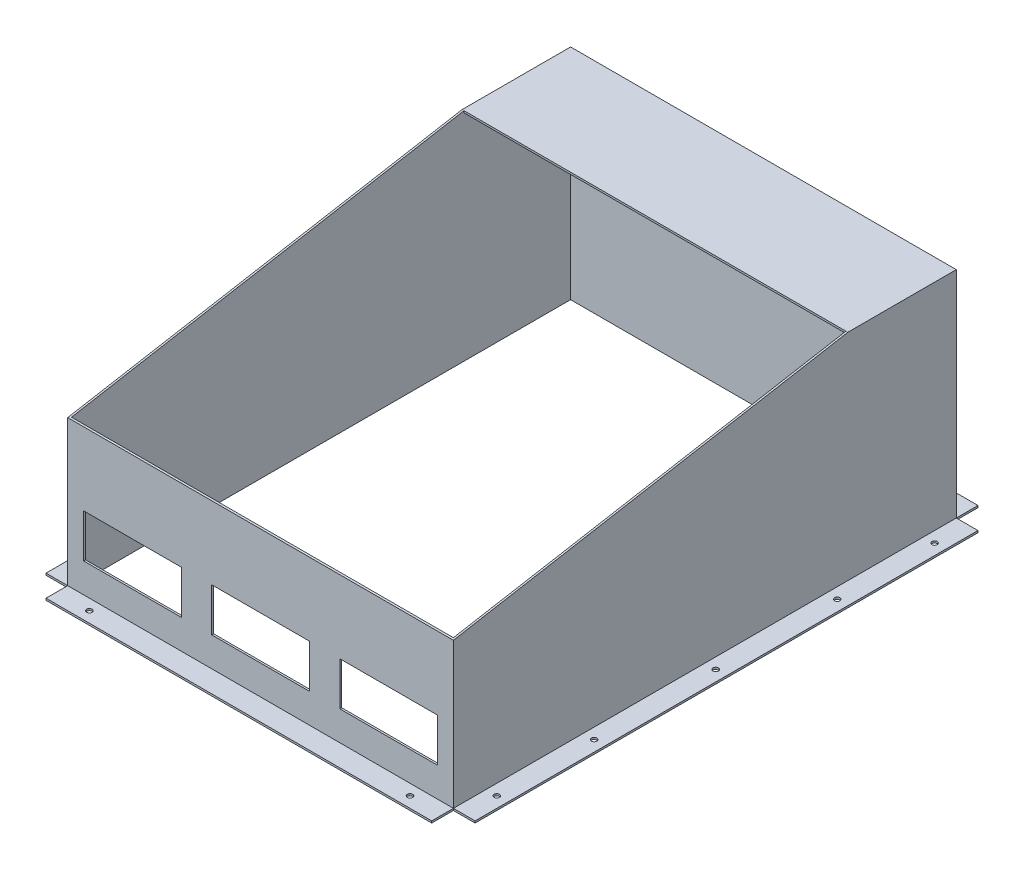
SolidWorks part; units mm, degrees
ref_plane "Alzado" through (0, 0, 0) normal (0, 0, 1) x (1, 0, 0)
ref_plane "Planta" through (0, 0, 0) normal (0, 1, 0) x (1, 0, 0)
ref_plane "Vista lateral" through (0, 0, 0) normal (1, 0, 0) x (0, 0, -1)
sketch "Croquis1" plane through (0, 0, 0) normal (0, 1, 0) x (1, 0, 0)
  line L1 (-177.75, 231.75) -> (177.75, 231.75)
  line L2 (-177.75, 231.75) -> (-177.75, -231.75)
  line L3 (-177.75, -231.75) -> (177.75, -231.75)
  line L4 (177.75, 231.75) -> (177.75, -231.75)
  line L5 (-177.75, 231.75) -> (177.75, -231.75) construction
  line L6 (-177.75, -231.75) -> (177.75, 231.75) construction
  point P0 (0, 0)
  dimension "D1" = 355.5
  dimension "D2" = 463.5
extrude "Saliente-Extruir1" add sketch "Croquis1" along normal blind 200
sketch "Croquis2" plane through (0, 200, 0) normal (0, 1, 0) x (1, 0, 0)
  line L0 (177.75, -231.75) -> (177.75, 231.75) construction
  line L1 (-176, 230) -> (176, 230)
  line L2 (-176, 230) -> (-176, -230)
  line L3 (-176, -230) -> (176, -230)
  line L4 (176, 230) -> (176, -230)
  line L5 (-176, 230) -> (176, -230) construction
  line L6 (-176, -230) -> (176, 230) construction
  line L7 (177.75, 231.75) -> (-177.75, 231.75) construction
  point P0 (0, 0)
  dimension "D1" = 1.75
  dimension "D2" = 1.75
extrude "Cortar-Extruir1" cut sketch "Croquis2" against normal blind 300
sketch "Croquis3" plane through (-177.75, 0, 0) normal (-1, 0, 0) x (0, 0, 1)
  line L0 (-131.75, 200) -> (231.75, 135.9051)
  line L1 (231.75, 200) -> (231.75, 0) construction
  line L2 (231.75, 135.9051) -> (231.75, 200)
  line L3 (231.75, 200) -> (-131.75, 200)
  line L4 (-231.75, 200) -> (231.75, 200) construction
  line L5 (-231.75, 200) -> (-231.75, 0) construction
  dimension "D1" = 10
  dimension "D2" = 100
extrude "Cortar-Extruir2" cut sketch "Croquis3" against normal through all
sketch "Croquis4" plane through (-177.75, 0, 0) normal (-1, 0, 0) x (0, 0, 1)
  line L0 (231.75, 135.9051) -> (231.75, 0) construction
  line L1 (-231.75, 0) -> (231.75, 0)
  line L2 (-231.75, 0) -> (-231.75, 1.75)
  line L3 (-231.75, 1.75) -> (231.75, 1.75)
  line L4 (231.75, 0) -> (231.75, 1.75)
  dimension "D1" = 1.75
extrude "Saliente-Extruir2" add sketch "Croquis4" along normal blind 20
sketch "Croquis5" plane through (177.75, 0, 0) normal (1, 0, 0) x (0, 0, -1)
  line L0 (231.75, 200) -> (231.75, 0) construction
  line L1 (-231.75, 0) -> (231.75, 0)
  line L2 (-231.75, 0) -> (-231.75, 1.75)
  line L3 (-231.75, 1.75) -> (231.75, 1.75)
  line L4 (231.75, 0) -> (231.75, 1.75)
  dimension "D1" = 1.75
extrude "Saliente-Extruir3" add sketch "Croquis5" along normal blind 20
sketch "Croquis6" plane through (0, 0, -231.75) normal (0, 0, -1) x (-1, 0, 0)
  line L0 (-197.75, 0) -> (197.75, 0) construction
  line L1 (-177.75, 1.75) -> (177.75, 1.75)
  line L2 (-177.75, 1.75) -> (-177.75, 0)
  line L3 (-177.75, 0) -> (177.75, 0)
  line L4 (177.75, 1.75) -> (177.75, 0)
extrude "Saliente-Extruir4" add sketch "Croquis6" along normal blind 20
sketch "Croquis7" plane through (0, 0, 231.75) normal (0, 0, 1) x (1, 0, 0)
  line L0 (-197.75, 0) -> (197.75, 0) construction
  line L1 (-177.75, 1.75) -> (177.75, 1.75)
  line L2 (-177.75, 1.75) -> (-177.75, 0)
  line L3 (-177.75, 0) -> (177.75, 0)
  line L4 (177.75, 1.75) -> (177.75, 0)
extrude "Saliente-Extruir5" add sketch "Croquis7" along normal blind 20
sketch "Croquis8" plane through (0, 1.75, 0) normal (0, 1, 0) x (1, 0, 0)
  line L0 (0, -251.75) -> (0, 251.75) construction
  line L1 (177.75, -251.75) -> (-177.75, -251.75) construction
  line L2 (-177.75, 251.75) -> (177.75, 251.75) construction
  line L3 (-197.75, 0) -> (197.75, 0) construction
  line L4 (-197.75, -231.75) -> (-197.75, 231.75) construction
  line L5 (197.75, 231.75) -> (197.75, -231.75) construction
  line L6 (187.75, -231.75) -> (187.75, 231.75) construction
  line L7 (197.75, -231.75) -> (177.75, -231.75) construction
  line L8 (197.75, 231.75) -> (177.75, 231.75) construction
  line L9 (177.75, 241.75) -> (-177.75, 241.75) construction
  line L10 (177.75, 251.75) -> (177.75, 231.75) construction
  line L11 (-177.75, 251.75) -> (-177.75, 231.75) construction
  line L12 (-187.75, 231.75) -> (-187.75, -231.75) construction
  line L13 (-197.75, 231.75) -> (-177.75, 231.75) construction
  line L14 (-197.75, -231.75) -> (-177.75, -231.75) construction
  line L15 (-177.75, -241.75) -> (177.75, -241.75) construction
  line L16 (-177.75, -251.75) -> (-177.75, -231.75) construction
  line L17 (177.75, -251.75) -> (177.75, -231.75) construction
  circle A0 centre (-187.75, 201.75) radius 2.5
  circle A1 centre (-187.75, 0) radius 2.5
  circle A2 centre (-187.75, 112) radius 2.5
  circle A3 centre (187.75, 201.75) radius 2.5
  circle A4 centre (187.75, 112) radius 2.5
  circle A5 centre (187.75, 0) radius 2.5
  circle A6 centre (-187.75, -201.75) radius 2.5
  circle A7 centre (-187.75, -112) radius 2.5
  circle A8 centre (187.75, -112) radius 2.5
  circle A9 centre (187.75, -201.75) radius 2.5
  circle A10 centre (0, 241.75) radius 2.5
  circle A11 centre (147.75, 241.75) radius 2.5
  circle A12 centre (-147.75, 241.75) radius 2.5
  circle A13 centre (147.75, -241.75) radius 2.5
  circle A14 centre (-147.75, -241.75) radius 2.5
  point P64 (0, -241.75)
  dimension "D1" = 5
  dimension "D3" = 5
  dimension "D4" = 5
  dimension "D6" = 5
  dimension "D7" = 5
  dimension "D2" = 30
  dimension "D5" = 112
  dimension "D8" = 30
extrude "Cortar-Extruir3" cut sketch "Croquis8" against normal blind 20
sketch "Croquis9" plane through (0, 0, 231.75) normal (0, 0, 1) x (1, 0, 0)
  line L0 (-177.75, 68.8276) -> (177.75, 68.8276) construction
  line L1 (-177.75, 135.9051) -> (-177.75, 1.75) construction
  line L2 (177.75, 135.9051) -> (177.75, 1.75) construction
  line L3 (0, 1.75) -> (0, 135.9051) construction
  line L4 (177.75, 1.75) -> (-177.75, 1.75) construction
  line L5 (177.75, 135.9051) -> (-177.75, 135.9051) construction
  line L6 (163, 28.8276) -> (73, 28.8276)
  line L7 (-45, 68.8276) -> (45, 68.8276)
  line L8 (-45, 68.8276) -> (-45, 28.8276)
  line L9 (-45, 28.8276) -> (45, 28.8276)
  line L10 (45, 68.8276) -> (45, 28.8276)
  line L11 (-163, 68.8276) -> (-73, 68.8276)
  line L12 (-163, 68.8276) -> (-163, 28.8276)
  line L13 (-163, 28.8276) -> (-73, 28.8276)
  line L14 (-73, 68.8276) -> (-73, 28.8276)
  line L15 (73, 68.8276) -> (73, 28.8276)
  line L16 (163, 68.8276) -> (73, 68.8276)
  line L17 (163, 68.8276) -> (163, 28.8276)
  dimension "D1" = 90
  dimension "D2" = 45
  dimension "D3" = 40
  dimension "D4" = 90
  dimension "D5" = 28
  dimension "D6" = 40
extrude "Cortar-Extruir4" cut sketch "Croquis9" against normal blind 20
sketch "Croquis10" plane through (0, 0, -230) normal (0, 0, 1) x (1, 0, 0)
  line L0 (176, 0) -> (176, 200) construction
  line L1 (-176, 200) -> (176, 200)
  line L2 (-176, 200) -> (-176, 198.25)
  line L3 (-176, 198.25) -> (176, 198.25)
  line L4 (176, 200) -> (176, 198.25)
  dimension "D1" = 1.75
extrude "Saliente-Extruir6" add sketch "Croquis10" along normal up to vertex (98.25 mm away) up to point (176, 200, -131.75)
